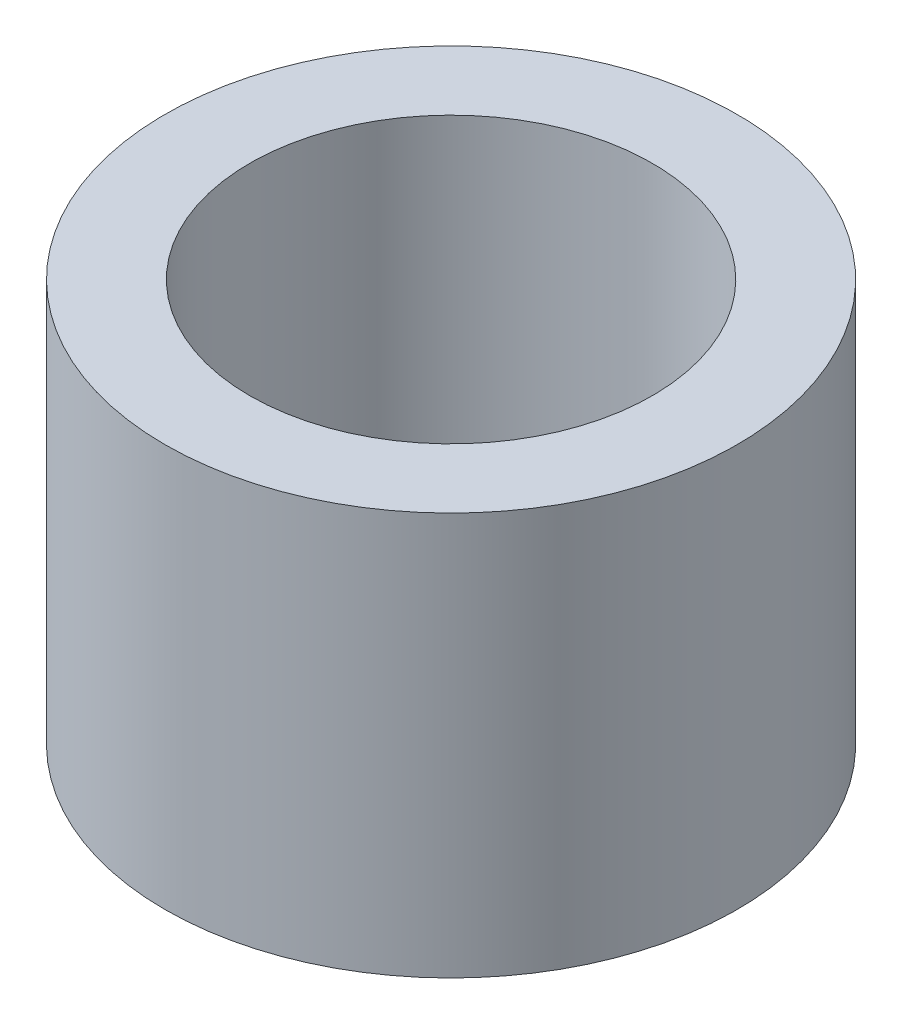
SolidWorks part; units mm, degrees
ref_plane "Спереди" through (0, 0, 0) normal (0, 0, 1) x (1, 0, 0)
ref_plane "Сверху" through (0, 0, 0) normal (0, 1, 0) x (1, 0, 0)
ref_plane "Справа" through (0, 0, 0) normal (1, 0, 0) x (0, 0, -1)
sketch "Эскиз1" plane through (0, 0, 0) normal (0, 1, 0) x (1, 0, 0)
  circle A0 centre (0, 0) radius 9.5
  circle A1 centre (0, 0) radius 13.5
  dimension "D1" = 19
  dimension "D2" = 4
extrude "Бобышка-Вытянуть1" add sketch "Эскиз1" along normal blind 19
